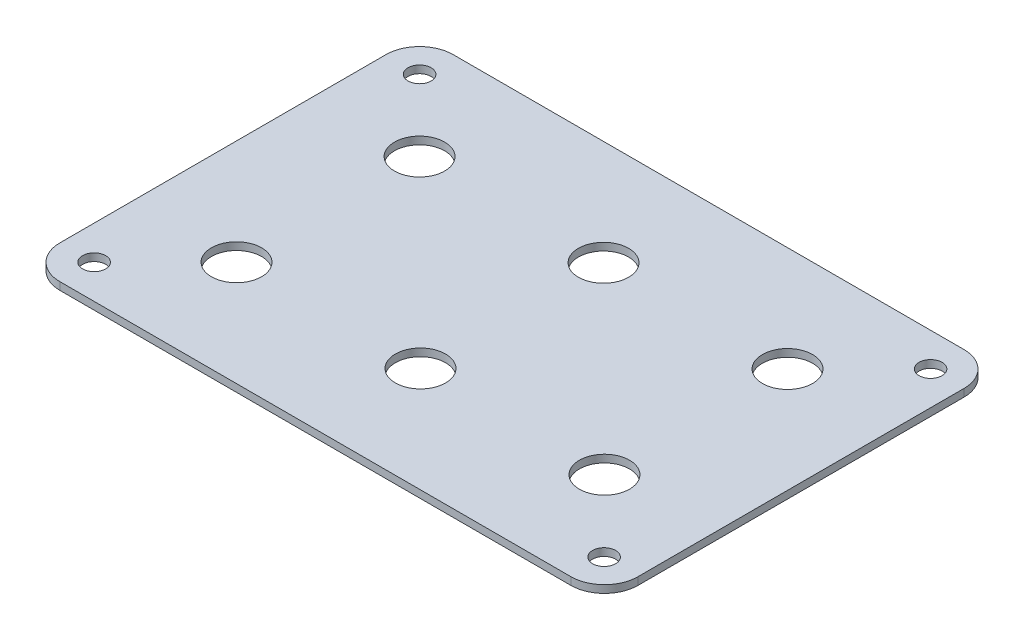
SolidWorks part; units mm, degrees
ref_plane "Front Plane" through (0, 0, 0) normal (0, 0, 1) x (1, 0, 0)
ref_plane "Top Plane" through (0, 0, 0) normal (0, 1, 0) x (1, 0, 0)
ref_plane "Right Plane" through (0, 0, 0) normal (1, 0, 0) x (0, 0, -1)
sketch "Sketch1" plane through (0, 0, 0) normal (0, 1, 0) x (1, 0, 0)
  line L0 (304.69, 389.3) -> (91.09, 389.3)
  line L1 (77.04, 403.35) -> (77.04, 539.66)
  line L2 (91.09, 553.71) -> (304.69, 553.71)
  line L3 (318.74, 539.66) -> (318.74, 403.35)
  circle A0 centre (120.98, 509.77) radius 10.49
  circle A1 centre (197.89, 509.77) radius 10.49
  circle A2 centre (274.81, 509.77) radius 10.49
  circle A3 centre (120.98, 433.24) radius 10.49
  circle A4 centre (197.89, 433.24) radius 10.49
  circle A5 centre (274.81, 433.24) radius 10.49
  circle A6 centre (91.22, 539.54) radius 4.82
  circle A7 centre (91.22, 403.48) radius 4.82
  circle A8 centre (304.57, 403.33) radius 4.82
  circle A9 centre (304.71, 539.68) radius 4.82
  spline S0 degree 3 poles (91.09, 389.3) (83.33, 389.3) (77.04, 395.59) (77.04, 403.35) knots 1 1 1 1 2 2 2 2
  spline S1 degree 3 poles (77.04, 539.66) (77.04, 547.42) (83.33, 553.71) (91.09, 553.71) knots 3 3 3 3 4 4 4 4
  spline S2 degree 3 poles (304.69, 553.71) (312.45, 553.71) (318.74, 547.42) (318.74, 539.66) knots 5 5 5 5 6 6 6 6
  spline S3 degree 3 poles (318.74, 403.35) (318.74, 395.59) (312.45, 389.3) (304.69, 389.3) knots 7 7 7 7 8 8 8 8
extrude "Boss-Extrude1" add sketch "Sketch1" along normal blind 3.175
